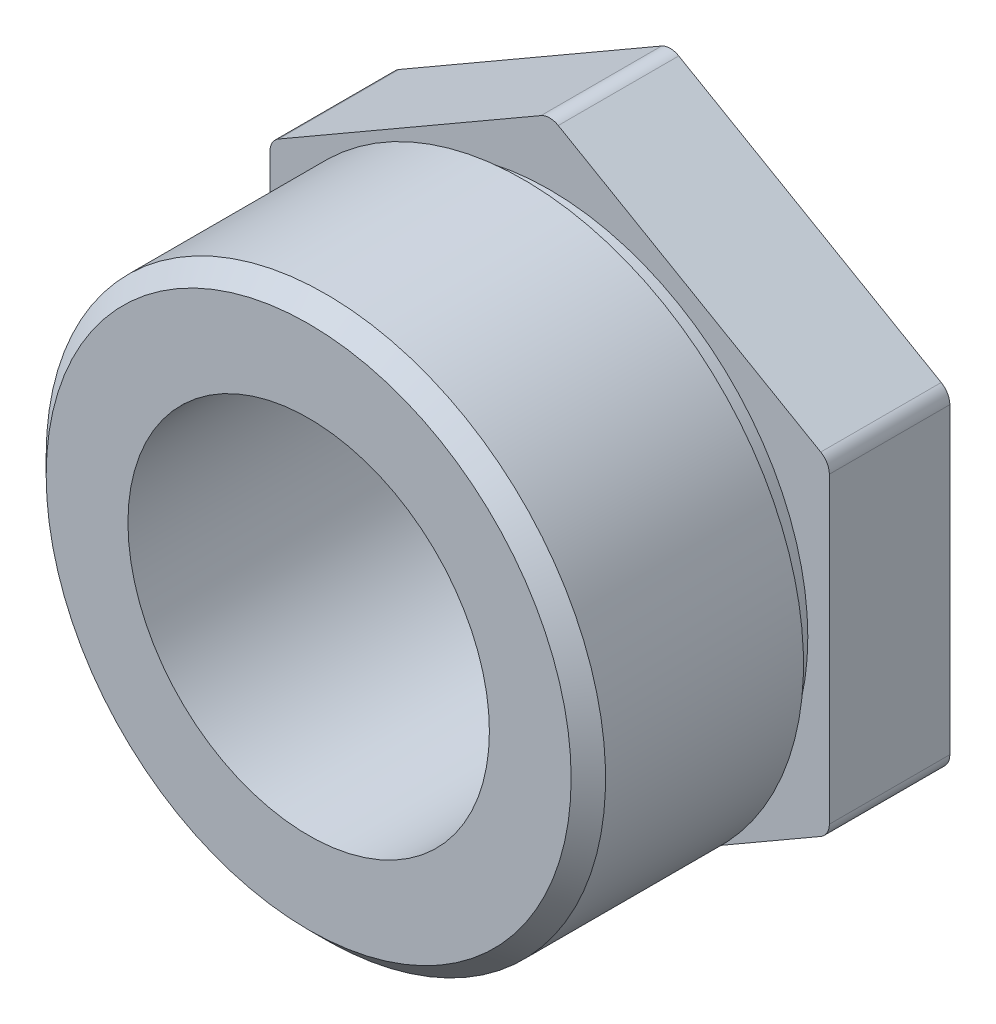
SolidWorks part; units mm, degrees
ref_plane "Front Plane" through (0, 0, 0) normal (0, 0, 1) x (1, 0, 0)
ref_plane "Top Plane" through (0, 0, 0) normal (0, 1, 0) x (1, 0, 0)
ref_plane "Right Plane" through (0, 0, 0) normal (1, 0, 0) x (0, 0, -1)
sketch "Sketch1" plane through (0, 0, 0) normal (0, 0, 1) x (1, 0, 0)
  circle A0 centre (0, 0) radius 32.5
  dimension "D1" = 65
extrude "Boss-Extrude1" add sketch "Sketch1" along normal blind 42
cosmetic thread "Cosmetic Thread1" parameters "D1"=25, "D2"=59.61
sketch "Sketch2" plane through (0, 0, 42) normal (0, 0, 1) x (1, 0, 0)
  circle A0 centre (0, 0) radius 30
  circle A1 centre (0, 0) radius 32.5
  circle A2 centre (0, 0) radius 32.5
  dimension "D2" = 60
  dimension "D1" = 0
extrude "Cut-Extrude1" cut sketch "Sketch2" along normal blind 3 from offset 28 offset against normal yes
sketch "Sketch3" plane through (0, 0, 0) normal (0, 0, -1) x (-1, 0, 0)
  line L1 (-32.5, 18.7639) -> (-32.5, -18.7639)
  line L2 (-32.5, -18.7639) -> (0, -37.5278)
  line L3 (0, -37.5278) -> (32.5, -18.7639)
  line L4 (32.5, -18.7639) -> (32.5, 18.7639)
  line L5 (32.5, 18.7639) -> (0, 37.5278)
  line L6 (0, 37.5278) -> (-32.5, 18.7639)
  circle A0 centre (0, 0) radius 32.5 construction
  circle A1 centre (0, 0) radius 32.5 construction
extrude "Boss-Extrude2" add sketch "Sketch3" against normal blind 14
fillet "Fillet1" radius 2 6 edges at (32.5, -18.7639, 7) (0, -37.5278, 7) (-32.5, -18.7639, 7) (-32.5, 18.7639, 7) (32.5, 18.7639, 7) (0, 37.5278, 7)
chamfer "Chamfer1" distance 2 angle 45 1 edges at (32.5, 0, 42)
sketch "Sketch4" plane through (0, 0, 42) normal (0, 0, 1) x (1, 0, 0)
  circle A0 centre (0, 0) radius 21
  dimension "D1" = 42
extrude "Cut-Extrude2" cut sketch "Sketch4" against normal through all
